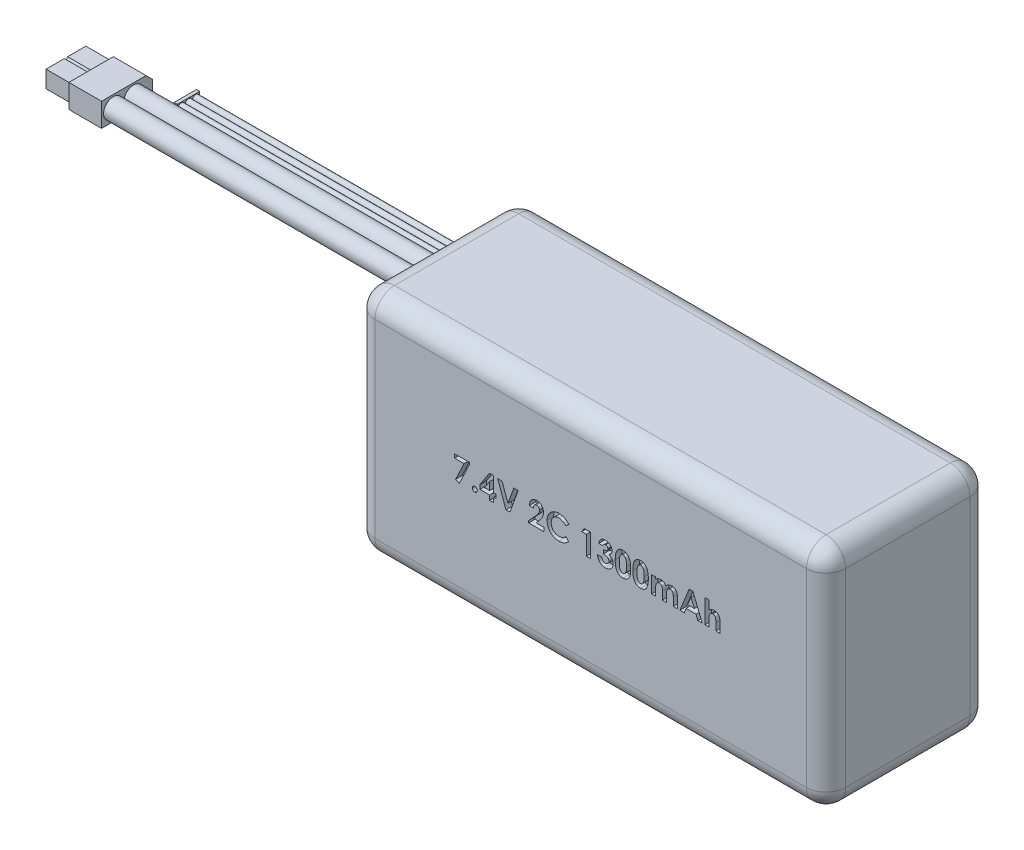
SolidWorks part; units mm, degrees
ref_plane "正面" through (0, 0, 0) normal (0, 0, 1) x (1, 0, 0)
ref_plane "平面" through (0, 0, 0) normal (0, 1, 0) x (1, 0, 0)
ref_plane "右側面" through (0, 0, 0) normal (1, 0, 0) x (0, 0, -1)
sketch "ｽｹｯﾁ1" plane through (0, 0, 0) normal (0, 0, 1) x (1, 0, 0)
  line L1 (36, -17.5) -> (-36, -17.5)
  line L2 (36, -17.5) -> (36, 17.5)
  line L3 (36, 17.5) -> (-36, 17.5)
  line L4 (-36, -17.5) -> (-36, 17.5)
  line L5 (36, -17.5) -> (-36, 17.5) construction
  line L6 (36, 17.5) -> (-36, -17.5) construction
  point P0 (0, 0)
  dimension "D1" = 72
  dimension "D2" = 35
extrude "ﾎﾞｽ - 押し出し1" add sketch "ｽｹｯﾁ1" along normal blind 25
fillet "ﾌｨﾚｯﾄ2" radius 3 12 edges at (0, 17.5, 25) (0, 17.5, 0) (36, 0, 25) (36, 17.5, 12.5) (36, 0, 0) (0, -17.5, 25) (36, -17.5, 12.5) (0, -17.5, 0) (-36, 17.5, 12.5) (-36, 0, 25) (-36, -17.5, 12.5) (-36, 0, 0)
sketch "ｽｹｯﾁ2" plane through (0, 0, 25) normal (0, 0, 1) x (1, 0, 0)
  text T0 "<b>7.4V 2C 1300mAh</b>"
extrude "ｶｯﾄ - 押し出し2" cut sketch "ｽｹｯﾁ2" against normal blind 1
sketch "ｽｹｯﾁ3" plane through (-36, 0, 0) normal (-1, 0, 0) x (0, 0, 1)
  line L0 (22, 14.5) -> (3, 14.5) construction
  line L1 (22, -14.5) -> (22, 14.5) construction
  circle A0 centre (17, 14.5) radius 1.5
  circle A1 centre (13.9, 14.5) radius 1.5
  dimension "D1" = 3
  dimension "D2" = 5
  dimension "D3" = 3.1
extrude "ﾎﾞｽ - 押し出し2" add sketch "ｽｹｯﾁ3" along normal blind 50 and the other way blind 5
sketch "ｽｹｯﾁ5" plane through (-86, 0, 0) normal (-1, 0, 0) x (0, 0, 1)
  line L1 (18.8, 16.3) -> (11, 16.3)
  line L2 (18.8, 16.3) -> (18.8, 12.7)
  line L3 (18.8, 12.7) -> (11, 12.7)
  line L4 (11, 16.3) -> (11, 12.7)
  arc A0 (18.5, 14.5) -> (15.5, 14.5) centre (17, 14.5) ccw construction
  circle A1 centre (17, 14.5) radius 1.5 construction
  dimension "D1" = 1.8
  dimension "D2" = 3.6
  dimension "D3" = 1.8
  dimension "D4" = 7.8
extrude "ﾎﾞｽ - 押し出し3" add sketch "ｽｹｯﾁ5" against normal blind 5
chamfer "面取り1" distance 1 angle 45 2 edges at (-83.5, 12.7, 11) (-83.5, 16.3, 11)
sketch3d "3Dｽｹｯﾁ1"
  line L0 (-86, 13.2, 18.3) -> (-86, 15.8, 18.3)
  line L1 (-86, 15.8, 18.3) -> (-86, 15.8, 12.2071)
  line L2 (-86, 15.0929, 11.5) -> (-86, 15.8, 12.2071)
  line L3 (-86, 15.8, 12.2071) -> (-86, 13.9071, 11.5)
  line L4 (-86, 13.2, 12.2071) -> (-86, 13.9071, 11.5)
  line L5 (-86, 13.9071, 11.5) -> (-86, 13.2, 18.3)
  line L6 (-86, 13.2, 18.3) -> (-86, 15.8, 18.3)
  line L7 (-86, 15.8, 18.3) -> (-86, 15.8, 12.2071)
  line L8 (-86, 15.0929, 11.5) -> (-86, 15.8, 12.2071)
  line L12 (-86, 13.2, 12.2071) -> (-86, 13.2, 18.3)
  line L13 (-86, 15.0929, 11.5) -> (-86, 13.9071, 11.5)
  line L14 (-86, 13.9071, 11.5) -> (-86, 13.2, 12.2071)
  line L15 (-86, 13.7, 11) -> (-86, 12.7, 12) construction
  line L16 (-86, 12.7, 12) -> (-86, 12.7, 18.8) construction
  dimension "D1" = 0.5
extrude "ﾎﾞｽ - 押し出し4" add sketch "3Dｽｹｯﾁ1" along direction (1, 0, 0) on the side against the normal blind 4 contours L6 L7 L8 L13 L14 L12
sketch "ｽｹｯﾁ6" plane through (-90, 0, 0) normal (-1, 0, 0) x (0, 0, 1)
  line L0 (15, 15.8) -> (15.25, 15.367)
  line L2 (15.25, 15.367) -> (15.5, 15.8)
  line L3 (18.3, 15.8) -> (12.2071, 15.8) construction
  line L4 (15.5, 15.8) -> (15, 15.8)
  line L5 (15, 13.2) -> (15.25, 13.633)
  line L7 (15.25, 13.633) -> (15.5, 13.2)
  line L8 (15.5, 13.2) -> (15, 13.2)
  line L9 (18.3, 13.2) -> (18.3, 15.8) construction
  line L10 (12.2071, 13.2) -> (18.3, 13.2) construction
  circle A0 centre (13.65, 14.5) radius 1
  circle A1 centre (16.85, 14.5) radius 1
  dimension "D3" = 2
  dimension "D4" = 1.3
  dimension "D5" = 1.6
  dimension "D6" = 1.6
  dimension "D1" = 2.8
  dimension "D2" = 0.5
extrude "ｶｯﾄ - 押し出し3" cut sketch "ｽｹｯﾁ6" against normal up to surface (4 mm away)
sketch "ｽｹｯﾁ7" plane through (-36, 0, 0) normal (-1, 0, 0) x (0, 0, 1)
  line L0 (12.4, 14.5) -> (3, 14.5) construction
  line L1 (3, 14.5) -> (3, -14.5) construction
  circle A0 centre (11.6, 14.5) radius 0.5
  circle A1 centre (10.5, 14.5) radius 0.5
  circle A2 centre (9.4, 14.5) radius 0.5
  dimension "D1" = 1
  dimension "D2" = 1.1
  dimension "D3" = 1.1
  dimension "D4" = 7.5
extrude "ﾎﾞｽ - 押し出し5" add sketch "ｽｹｯﾁ7" along normal blind 40 and the other way blind 4
sketch "ｽｹｯﾁ8" plane through (-76, 0, 0) normal (-1, 0, 0) x (0, 0, 1)
  line L1 (12.2, 15.1) -> (8.8, 15.1)
  line L2 (12.2, 15.1) -> (12.2, 13.9)
  line L3 (12.2, 13.9) -> (8.8, 13.9)
  line L4 (8.8, 15.1) -> (8.8, 13.9)
  circle A0 centre (9.4, 14.5) radius 0.5 construction
  circle A1 centre (11.6, 14.5) radius 0.5 construction
  dimension "D1" = 0.6
  dimension "D2" = 1.2
  dimension "D3" = 0.6
  dimension "D4" = 0.6
extrude "ﾎﾞｽ - 押し出し6" add sketch "ｽｹｯﾁ8" along normal blind 0.5
